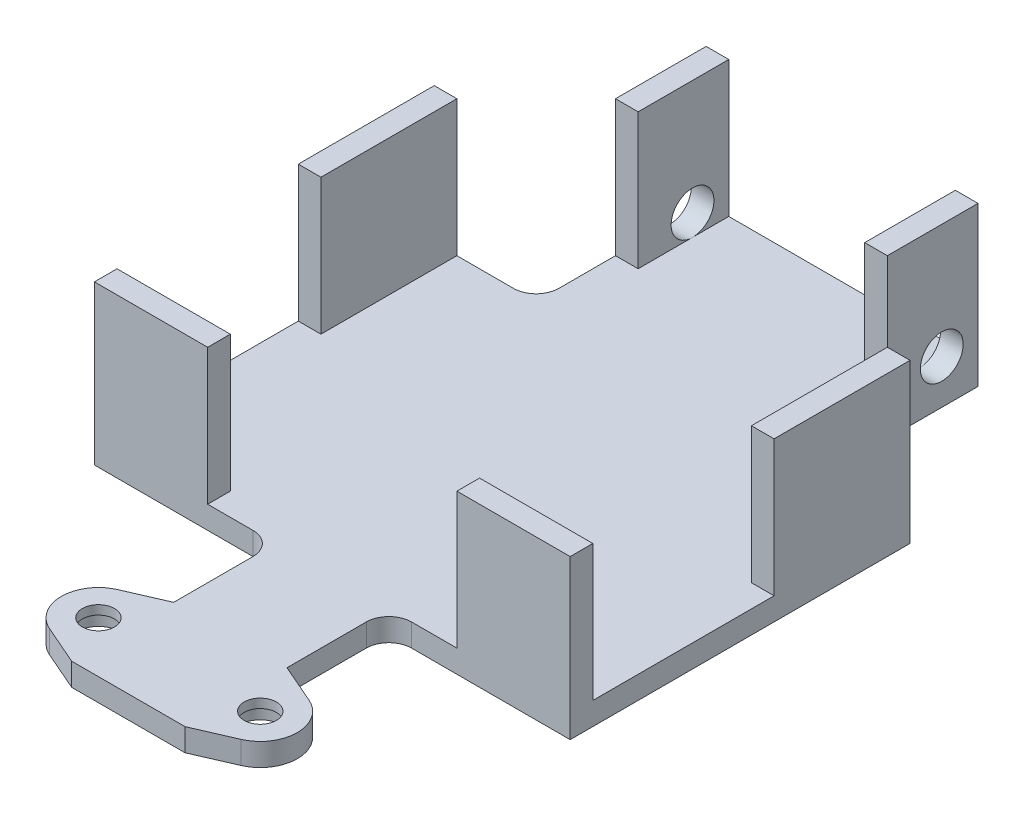
SolidWorks part; units mm, degrees
material "Custom Plastic"
ref_plane "Front Plane" through (0, 0, 0) normal (0, 0, 1) x (1, 0, 0)
ref_plane "Top Plane" through (0, 0, 0) normal (0, 1, 0) x (1, 0, 0)
ref_plane "Right Plane" through (0, 0, 0) normal (1, 0, 0) x (0, 0, -1)
sketch "Sketch1" plane through (0, 0, 0) normal (0, 1, 0) x (1, 0, 0)
  line L0 (50.8, 0) -> (50.8, -28.575)
  line L1 (0, 0) -> (50.8, 0)
  line L2 (0, 0) -> (0, 95.25)
  line L3 (0, 95.25) -> (28.575, 95.25)
  line L4 (133.35, 0) -> (133.35, 95.25)
  line L5 (28.575, 142.875) -> (104.775, 142.875)
  line L6 (28.575, 142.875) -> (28.575, 95.25)
  line L7 (50.8, -57.15) -> (82.55, -57.15)
  line L8 (104.775, 142.875) -> (104.775, 95.25)
  line L9 (104.775, 95.25) -> (133.35, 95.25)
  line L10 (82.55, 0) -> (133.35, 0)
  line L12 (82.55, -28.575) -> (93.4979, -33.3375)
  line L13 (82.55, 0) -> (82.55, -28.575)
  line L14 (66.675, -57.15) -> (66.675, 142.875) construction
  line L15 (50.8, -28.575) -> (39.8521, -33.3375)
  line L16 (50.8, -57.15) -> (39.8521, -52.3875)
  line L17 (93.4979, -52.3875) -> (93.4979, -33.3375) construction
  line L18 (82.55, -57.15) -> (82.55, -28.575) construction
  line L19 (93.4979, -52.3875) -> (82.55, -57.15)
  arc A0 (93.4979, -52.3875) -> (93.4979, -33.3375) centre (89.3544, -42.8625) ccw
  circle A1 centre (89.3544, -42.8625) radius 6
  circle A2 centre (43.9956, -42.8625) radius 6
  arc A3 (39.8521, -52.3875) -> (39.8521, -33.3375) centre (43.9956, -42.8625) cw
  point P5 (38.1, 31.75)
  dimension "D10" = 12
  dimension "D1" = 95.25
  dimension "D2" = 133.35
  dimension "D3" = 47.625
  dimension "D4" = 28.575
  dimension "D5" = 31.75
  dimension "D8" = 19.05
  dimension "D9" = 4.7625
  dimension "D11" = 28.575
extrude "Boss-Extrude1" add sketch "Sketch1" along normal blind 6.35
sketch "Sketch2" plane through (0, 6.35, 0) normal (0, 1, 0) x (1, 0, 0)
  line L1 (133.35, 57.15) -> (127, 57.15)
  line L2 (133.35, 57.15) -> (133.35, 95.25)
  line L3 (133.35, 95.25) -> (127, 95.25)
  line L4 (127, 57.15) -> (127, 95.25)
  line L5 (133.35, 57.15) -> (127, 95.25) construction
  line L6 (133.35, 95.25) -> (127, 57.15) construction
  line L12 (66.675, 142.875) -> (66.675, -57.15) construction
  line L13 (28.575, 142.875) -> (104.775, 142.875) construction
  line L14 (50.8, -57.15) -> (82.55, -57.15) construction
  line L15 (104.775, 95.25) -> (133.35, 95.25) construction
  line L16 (133.35, 0) -> (133.35, 95.25) construction
  line L17 (0, 95.25) -> (6.35, 57.15) construction
  line L18 (0, 57.15) -> (6.35, 95.25) construction
  line L19 (6.35, 57.15) -> (6.35, 95.25)
  line L20 (0, 95.25) -> (6.35, 95.25)
  line L21 (0, 57.15) -> (0, 95.25)
  line L22 (0, 57.15) -> (6.35, 57.15)
  line L24 (0, 0) -> (31.75, 0)
  line L25 (0, 0) -> (0, 6.35)
  line L26 (0, 6.35) -> (31.75, 6.35)
  line L27 (31.75, 0) -> (31.75, 6.35)
  line L28 (133.35, 0) -> (101.6, 0)
  line L29 (133.35, 0) -> (133.35, 6.35)
  line L30 (133.35, 6.35) -> (101.6, 6.35)
  line L31 (101.6, 0) -> (101.6, 6.35)
  point P0 (130.175, 76.2)
  point P19 (3.175, 76.2)
  dimension "D1" = 38.1
  dimension "D2" = 6.35
  dimension "D3" = 31.75
  dimension "D4" = 6.35
extrude "MotorMount" add sketch "Sketch2" along normal blind 38.1 contours L3 L4 L1 L2
sketch "Sketch4" plane through (0, 6.35, 0) normal (0, 1, 0) x (1, 0, 0)
  line L0 (82.55, 0) -> (82.55, -28.575) construction
  line L1 (104.775, 142.875) -> (98.425, 142.875)
  line L2 (104.775, 142.875) -> (104.775, 117.475)
  line L3 (104.775, 117.475) -> (98.425, 117.475)
  line L4 (98.425, 142.875) -> (98.425, 117.475)
  line L5 (82.55, -57.15) -> (98.425, -57.15)
  line L6 (82.55, -57.15) -> (82.55, -31.75)
  line L7 (82.55, -31.75) -> (98.425, -31.75)
  line L8 (98.425, -57.15) -> (98.425, -31.75)
  line L9 (50.8, -57.15) -> (82.55, -57.15) construction
  line L10 (66.675, 142.875) -> (66.675, -57.15) construction
  line L11 (28.575, 142.875) -> (104.775, 142.875) construction
  line L12 (50.8, -57.15) -> (34.925, -57.15)
  line L13 (50.8, -57.15) -> (50.8, -31.75)
  line L14 (34.925, -57.15) -> (34.925, -31.75)
  line L15 (50.8, -31.75) -> (34.925, -31.75)
  line L16 (28.575, 142.875) -> (28.575, 117.475)
  line L17 (28.575, 142.875) -> (34.925, 142.875)
  line L18 (34.925, 142.875) -> (34.925, 117.475)
  line L19 (28.575, 117.475) -> (34.925, 117.475)
  line M17 (104.775, 95.25) -> (104.775, 142.875)
  line M18 (104.775, 142.875) -> (28.575, 142.875)
  line M19 (28.575, 142.875) -> (28.575, 95.25)
  dimension "D1" = 25.4
  dimension "D2" = 6.35
extrude "WheelMounts" add sketch "Sketch4" along normal blind 38.1 contours L4 L3 M18 M17 | L19 L18 M19 M18
fillet "Fillet1" radius 6.35 2 edges at (50.8, 3.175, 0) (82.55, 3.175, 0)
sketch "Sketch5" plane through (0, 6.35, 0) normal (0, 1, 0) x (1, 0, 0)
  circle A0 centre (43.9956, -42.8625) radius 6
  circle A1 centre (89.3544, -42.8625) radius 6
  circle A2 centre (89.3544, -42.8625) radius 6 construction
  circle A3 centre (43.9956, -42.8625) radius 6 construction
  circle A4 centre (43.9956, -42.8625) radius 4.5
  circle A5 centre (89.3544, -42.8625) radius 4.5
  dimension "D1" = 9
  dimension "D2" = 9
extrude "Boss-Extrude4" add sketch "Sketch5" against normal blind 2.54 contours A1
sketch "Sketch6" plane through (104.775, 0, 0) normal (1, 0, 0) x (0, 0, -1)
  line L0 (132.715, 12.35) -> (132.715, 44.45) construction
  line L1 (117.475, 44.45) -> (142.875, 44.45) construction
  line L2 (142.875, 6.35) -> (117.475, 6.35) construction
  line L5 (142.875, 44.45) -> (142.875, 0) construction
  circle A0 centre (132.715, 12.35) radius 6
  point P2 (0, 0)
  point P9 (0, 0)
  point P10 (0, 0)
  point P11 (0, 0)
  point P14 (0, 0)
  dimension "D1" = 12
  dimension "D2" = 10.16
extrude "Cut-Extrude2" cut sketch "Sketch6" against normal blind 83.947 contours A0
sketch "Sketch7" plane through (104.775, 0, 0) normal (1, 0, 0) x (0, 0, -1)
  circle A0 centre (132.715, 12.35) radius 27
  dimension "D1" = 54
fillet "Fillet2" radius 6.35 2 edges at (28.575, 3.175, -95.25) (104.775, 3.175, -95.25)
